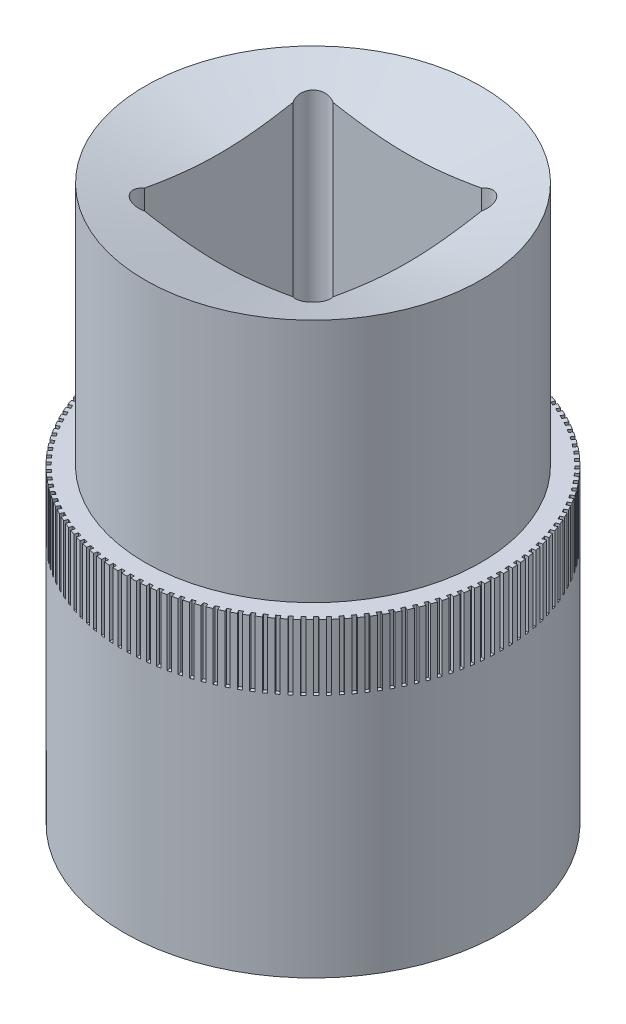
SolidWorks part; units mm, degrees
ref_plane "Front Plane" through (0, 0, 0) normal (0, 0, 1) x (1, 0, 0)
ref_plane "Top Plane" through (0, 0, 0) normal (0, 1, 0) x (1, 0, 0)
ref_plane "Right Plane" through (0, 0, 0) normal (1, 0, 0) x (0, 0, -1)
sketch "Sketch1" plane through (0, 0, 0) normal (1, 0, 0) x (0, 0, -1)
  line L0 (0, 19) -> (0, -19) construction
  line L1 (11.5, 19) -> (11.5, 2.25)
  line L2 (11.5, 2.25) -> (12.925, 2.25)
  line L3 (12.925, 2.25) -> (12.925, -19)
  line L4 (12.925, -19) -> (10, -19)
  line L5 (10, -19) -> (10, -0.8)
  line L6 (10, -0.8) -> (6.45, -0.8)
  line L7 (6.45, -0.8) -> (6.45, 17.5)
  line L8 (6.45, 17.5) -> (11.5, 19)
  line L9 (0, -19) -> (10, -19) construction
  line L10 (0, 19) -> (11.5, 19) construction
  dimension "D1" = 38
  dimension "D2" = 23
  dimension "D3" = 12.9
  dimension "D4" = 1.5
  dimension "D5" = 20
  dimension "D6" = 25.85
  dimension "D7" = 21.25
  dimension "D8" = 16.75
  dimension "D9" = 18.3
revolve "Revolve1" add sketch "Sketch1" angle 360 about L0
ref_plane "Plane1" through (0, 19, 0) normal (0, 1, 0) x (1, 0, 0)
sketch "Sketch2" plane through (0, 19, 0) normal (0, 1, 0) x (1, 0, 0)
  line L0 (-5.5861, 5.5861) -> (5.5861, -5.5861) construction
  line L1 (-5.0824, 6.45) -> (5.0824, 6.45)
  line L2 (-6.45, 5.0824) -> (-6.45, -5.0824)
  line L3 (-5.0824, -6.45) -> (5.0824, -6.45)
  line L4 (6.45, 5.0824) -> (6.45, -5.0824)
  line L5 (5.5861, 5.5861) -> (-5.5861, -5.5861) construction
  line L6 (-5.5861, 5.5861) -> (5.5861, 5.5861) construction
  line L7 (5.5861, 5.5861) -> (5.5861, -5.5861) construction
  line L8 (5.5861, -5.5861) -> (-5.5861, -5.5861) construction
  line L9 (-5.5861, -5.5861) -> (-5.5861, 5.5861) construction
  arc A2 (6.45, 5.0824) -> (5.0824, 6.45) centre (5.5861, 5.5861) ccw
  arc A3 (5.0824, -6.45) -> (6.45, -5.0824) centre (5.5861, -5.5861) ccw
  arc A4 (-6.45, -5.0824) -> (-5.0824, -6.45) centre (-5.5861, -5.5861) ccw
  arc A5 (-5.0824, 6.45) -> (-6.45, 5.0824) centre (-5.5861, 5.5861) ccw
  circle A6 centre (0, 0) radius 6.45 construction
  point P0 (0, 0)
  point P7 (0, -6.45)
  point P8 (6.45, 0)
  dimension "D1" = 2
  dimension "D4" = 15.8
extrude "Cut-Extrude1" cut sketch "Sketch2" against normal blind 16
sketch "Sketch3" plane through (0, -19, 0) normal (0, -1, 0) x (1, 0, 0)
  line L0 (0, 0) -> (11.1, 0) construction
  line L1 (11.1, 0) -> (9.6129, 2.5758)
  line L2 (5.55, 9.6129) -> (2.5758, 9.6129)
  line L3 (-5.55, 9.6129) -> (-7.0371, 7.0371)
  line L4 (-11.1, 0) -> (-9.6129, -2.5758)
  line L5 (-5.55, -9.6129) -> (-2.5758, -9.6129)
  line L6 (5.55, -9.6129) -> (7.0371, -7.0371)
  line L7 (9.6129, 5.55) -> (7.0371, 7.0371)
  line L8 (0, 11.1) -> (-2.5758, 9.6129)
  line L9 (-9.6129, 5.55) -> (-9.6129, 2.5758)
  line L10 (-9.6129, -5.55) -> (-7.0371, -7.0371)
  line L11 (0, -11.1) -> (2.5758, -9.6129)
  line L12 (9.6129, -5.55) -> (9.6129, -2.5758)
  line L13 (9.6129, 5.55) -> (0, 0) construction
  line L14 (-9.6129, 2.5758) -> (-11.1, 0)
  line L15 (-9.6129, -2.5758) -> (-9.6129, -5.55)
  line L16 (-7.0371, -7.0371) -> (-5.55, -9.6129)
  line L17 (-2.5758, -9.6129) -> (0, -11.1)
  line L18 (2.5758, -9.6129) -> (5.55, -9.6129)
  line L19 (7.0371, -7.0371) -> (9.6129, -5.55)
  line L20 (9.6129, -2.5758) -> (11.1, 0)
  line L21 (9.6129, 2.5758) -> (9.6129, 5.55)
  line L22 (7.0371, 7.0371) -> (5.55, 9.6129)
  line L23 (2.5758, 9.6129) -> (0, 11.1)
  line L24 (-2.5758, 9.6129) -> (-5.55, 9.6129)
  line L25 (-7.0371, 7.0371) -> (-9.6129, 5.55)
  point P8 (9.3714, 5.55)
  point P25 (11.0483, 0.0895)
  dimension "D1" = 30
  dimension "D2" = 22.2
  dimension "D3" = 22.2
extrude "Cut-Extrude2" cut sketch "Sketch3" against normal blind 18.5
sketch "Sketch4" plane through (0, 0, 0) normal (1, 0, 0) x (0, 0, -1)
  line L0 (12.925, 2.25) -> (-12.925, 2.25) construction
  line L1 (-0.125, -2.25) -> (0.125, -2.25)
  line L2 (-0.125, -2.25) -> (-0.125, 2.25)
  line L3 (-0.125, 2.25) -> (0.125, 2.25)
  line L4 (0.125, -2.25) -> (0.125, 2.25)
  line L5 (-0.125, -2.25) -> (0.125, 2.25) construction
  line L6 (-0.125, 2.25) -> (0.125, -2.25) construction
  point P0 (0, 0)
  dimension "D1" = 0.25
extrude "Cut-Extrude3" cut sketch "Sketch4" against normal blind 0.25 from surface starting at face at (0, 2.25, 12.925)
pattern_circular "CirPattern1" count 130 over 360 about axis through (0, 0, 0) along (0, 1, 0) of "Cut-Extrude3"
